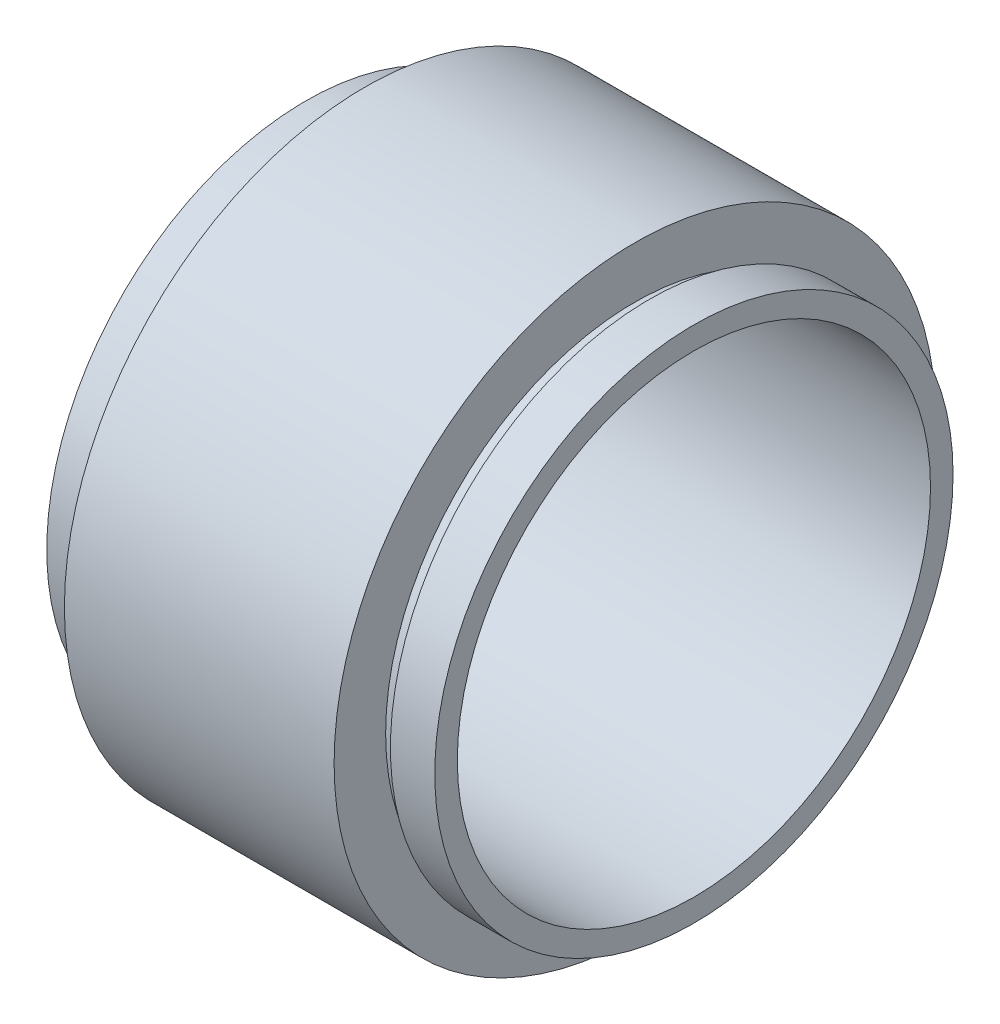
SolidWorks part; units mm, degrees
ref_plane "Front Plane" through (0, 0, 0) normal (0, 0, 1) x (1, 0, 0)
ref_plane "Top Plane" through (0, 0, 0) normal (0, 1, 0) x (1, 0, 0)
ref_plane "Right Plane" through (0, 0, 0) normal (1, 0, 0) x (0, 0, -1)
sketch "Sketch2" plane through (0, 0, 0) normal (0, 0, 1) x (1, 0, 0)
  line L0 (9.84, 0) -> (-9.84, 0)
  line L1 (-9.84, 0) -> (-9.84, 13.1445)
  line L2 (-9.84, 13.1445) -> (-7.59, 13.1445)
  line L3 (-7.59, 13.1445) -> (-7.59, 12.6365)
  line L4 (-7.59, 12.6365) -> (-6.84, 12.6365)
  line L5 (-6.84, 12.6365) -> (-6.84, 15.25)
  line L6 (-6.84, 15.25) -> (6.84, 15.25)
  line L7 (6.84, 15.25) -> (6.84, 12.6365)
  line L8 (6.84, 12.6365) -> (7.59, 12.6365)
  line L9 (7.59, 12.6365) -> (7.59, 13.1445)
  line L10 (7.59, 13.1445) -> (9.84, 13.1445)
  line L11 (9.84, 13.1445) -> (9.84, 0)
  point P3 (0, 15.25)
  dimension "D1" = 15.25
  dimension "D2" = 13.1445
  dimension "D3" = 0.508
  dimension "D4" = 13.68
  dimension "D5" = 0.75
  dimension "D6" = 3
revolve "Revolve1" add sketch "Sketch2" angle 360 about L0
sketch "Sketch3" plane through (-9.84, 0, 0) normal (-1, 0, 0) x (0, 0, 1)
  circle A0 centre (0, 0) radius 12
  dimension "D1" = 24
extrude "Cut-Extrude1" cut sketch "Sketch3" against normal through all
